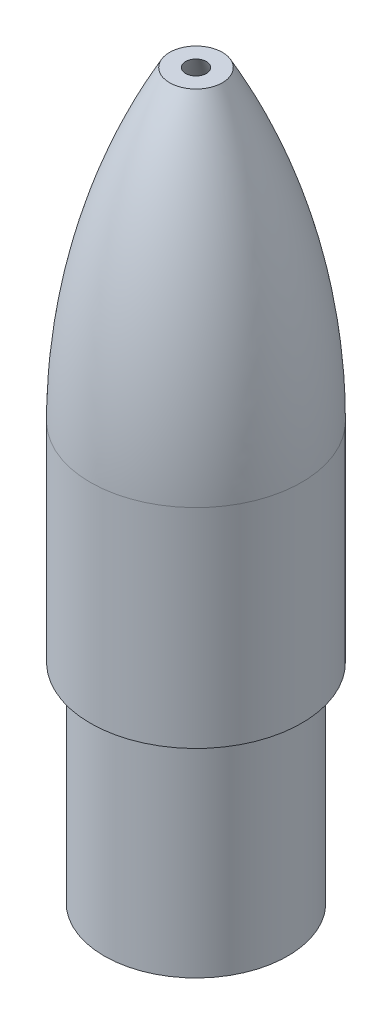
SolidWorks part; units mm, degrees
material "A-Glass Fiber"
ref_plane "Front Plane" through (0, 0, 0) normal (0, 0, 1) x (1, 0, 0)
ref_plane "Top Plane" through (0, 0, 0) normal (0, 1, 0) x (1, 0, 0)
ref_plane "Right Plane" through (0, 0, 0) normal (1, 0, 0) x (0, 0, -1)
sketch "Sketch1" plane through (0, 0, 0) normal (0, 0, 1) x (1, 0, 0)
  line L0 (76, -0.3445) -> (76, 149.6555)
  line L2 (66, -0.3445) -> (66, 149.6555)
  line L4 (66, -0.3445) -> (76, -0.3445)
  line L5 (0.7733, 400) -> (0.752, 381.3992)
  line L6 (0, -198.8179) -> (0, -350.074)
  spline S0 degree 4 poles (-14.3224, 421.4741) (-13.9912, 421.0307) (-13.33, 420.1427) (-12.3421, 418.8067) (-11.0351, 417.0212) (-9.74, 415.2335) (-8.4643, 413.4552) (-7.1936, 411.6645) (-5.9557, 409.9039) (-4.69, 408.0824) (-3.5044, 406.3634) (-2.1854, 404.4234) (-1.159, 402.9077) (0.3538, 400.6358) (1.0423, 399.5946) (2.2845, 397.7006) (3.2512, 396.2112) (4.2171, 394.7101) (5.1946, 393.1784) (6.1585, 391.6542) (7.1178, 390.1239) (8.0763, 388.5814) (9.0337, 387.0267) (16.961, 374.037) (28.5718, 353.0149) (42.4165, 323.2587) (56.9252, 282.3312) (67.374, 242.0803) (72.6485, 209.22) (74.898, 183.9236) (75.5875, 169.1734) (75.7118, 165.9556) (75.7993, 163.2083) (75.8498, 161.393) (75.8929, 159.5874) (75.9288, 157.7843) (75.9575, 155.9674) (75.9791, 154.1829) (75.9934, 152.4065) (76.001, 150.1399) (76.0004, 148.8889) (75.9904, 146.1484) (75.9694, 144.3126) (75.9379, 141.9551) (75.8959, 139.8598) (75.8434, 137.6322) (75.7804, 135.4723) (75.7066, 133.2683) (75.6218, 131.0723) (75.5259, 128.8575) (75.4186, 126.638) (75.33, 124.9717) (75.2673, 123.8618) (75.235, 123.3069) knots 0 0 0 0 0 0.006969 0.013937 0.020906 0.027875 0.034717 0.04156 0.048403 0.055246 0.062088 0.068931 0.075774 0.082616 0.0883 0.093983 0.099666 0.10535 0.111033 0.116716 0.122399 0.128083 0.133891 0.1397 0.313954 0.430124 0.546294 0.685698 0.836718 0.848335 0.865761 0.871569 0.877253 0.882936 0.888619 0.894302 0.899986 0.905669 0.911352 0.917035 0.923907 0.930779 0.93765 0.944522 0.951393 0.958265 0.965136 0.972008 0.979006 0.986004 0.993002 1 1 1 1 1 construction
  spline S1 degree 4 poles (0.7733, 400) (0.981, 399.6857) (1.3981, 399.0522) (2.2845, 397.7006) (3.2512, 396.2112) (4.2171, 394.7101) (5.1946, 393.1784) (6.1585, 391.6542) (7.1178, 390.1239) (8.0763, 388.5814) (9.0337, 387.0267) (16.961, 374.037) (28.5718, 353.0149) (42.4165, 323.2587) (56.9252, 282.3312) (67.374, 242.0803) (72.6485, 209.22) (74.898, 183.9236) (75.5875, 169.1734) (75.7118, 165.9556) (75.7993, 163.2083) (75.8498, 161.393) (75.8929, 159.5874) (75.9288, 157.7843) (75.9575, 155.9674) (75.9791, 154.1829) (75.9934, 152.4065) (75.9988, 150.791) (76, 150.0323) (76, 149.6555) knots 0.082616 0.082616 0.082616 0.082616 0.082616 0.0883 0.093983 0.099666 0.10535 0.111033 0.116716 0.122399 0.128083 0.133891 0.1397 0.313954 0.430124 0.546294 0.685698 0.836718 0.848335 0.865761 0.871569 0.877253 0.882936 0.888619 0.894302 0.899986 0.905669 0.911352 0.917035 0.917035 0.917035 0.917035 0.917035
  spline S2 degree 1 poles (-7.5703, 394.4879) (66, 149.6555) knots 0 0 1 1 construction
  spline S3 degree 3 poles (-7.5703, 394.4879) (-7.4069, 394.2405) (-7.1062, 393.784) (-6.5044, 392.8667) (-5.8965, 391.936) (-5.3415, 391.0813) (-4.8007, 390.2438) (-4.0754, 389.1152) (-2.7984, 387.1137) (-1.0054, 384.26) (3.2453, 377.3566) (12.107, 362.1999) (29.3937, 328.5343) (48.7231, 277.9338) (60.487, 225.0599) (64.6205, 187.4419) (65.5812, 169.911) (65.8398, 161.808) (65.9168, 158.4387) (65.9546, 156.0647) (65.9715, 154.7234) (65.9819, 153.7264) (65.99, 152.7071) (65.9957, 151.5956) (65.9992, 150.4988) (66, 149.952) (66, 149.6555) knots 0.082616 0.082616 0.082616 0.082616 0.085876 0.089135 0.092395 0.095654 0.098914 0.102173 0.108692 0.12173 0.134768 0.186919 0.291221 0.499826 0.708431 0.812733 0.864884 0.877922 0.89096 0.897479 0.900738 0.903998 0.907257 0.910517 0.913776 0.917035 0.917035 0.917035 0.917035 only from (0.752, 381.3992) to (66, 149.6555)
  point P11 (0.7733, 400)
  dimension "D1" = 400
  dimension "D2" = 150
  dimension "D3" = 150
  dimension "D5" = 76
  dimension "D4" = 10
revolve "Revolve3" add sketch "Sketch1" angle 360 about L6
ref_plane "Plane1" through (0, 149.6555, 0) normal (0, 1, 0) x (1, 0, 0)
sketch "Sketch2" plane through (0, 149.6555, 0) normal (0, 1, 0) x (1, 0, 0)
  circle A0 centre (0, 0) radius 66 construction
  circle A1 centre (0, 0) radius 66
  circle A2 centre (0, 0) radius 58
  dimension "D1" = 8
extrude "Boss-Extrude1" add sketch "Sketch2" against normal blind 300
ref_plane "Plane2" through (0, 400, 0) normal (0, -1, 0) x (-1, 0, 0)
sketch "Sketch3" plane through (0, 400, 0) normal (0, -1, 0) x (-1, 0, 0)
  circle A0 centre (0, 0) radius 132.2448
extrude "Cut-Extrude1" cut sketch "Sketch3" along normal blind 30
